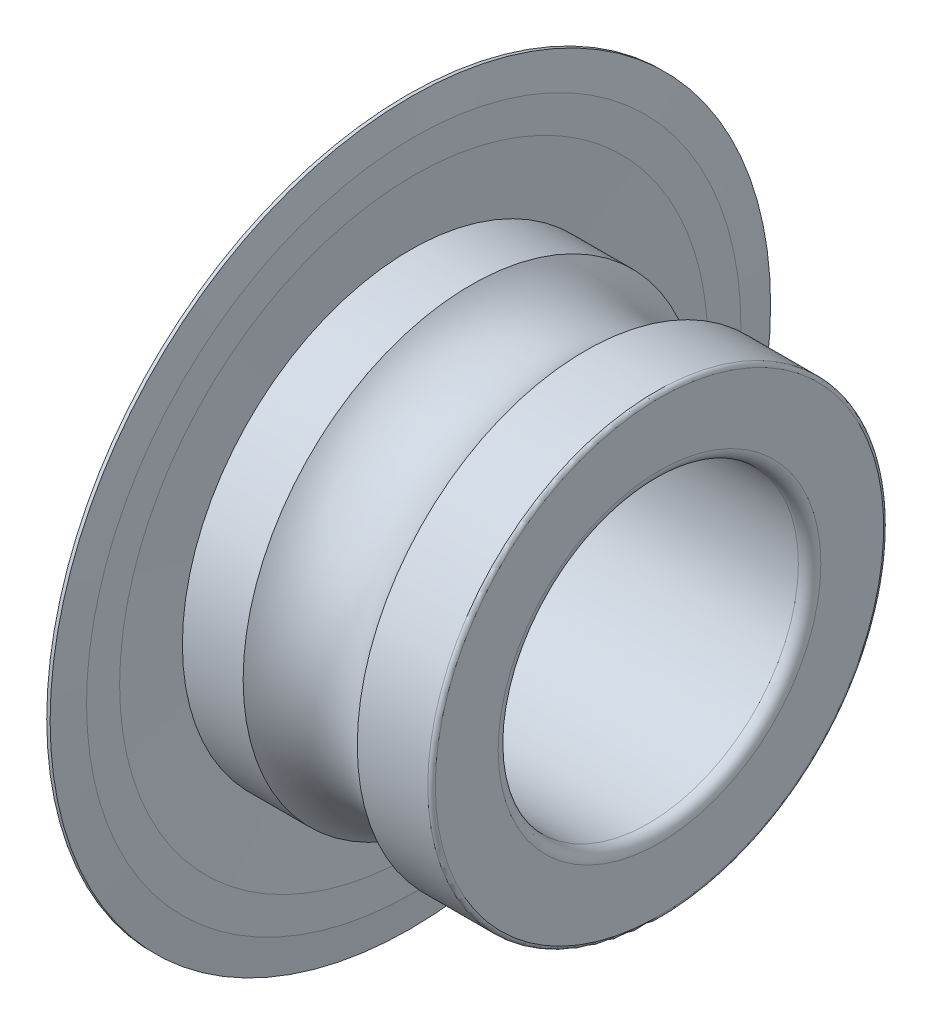
SolidWorks part; units mm, degrees
ref_plane "Front Plane" through (0, 0, 0) normal (0, 0, 1) x (1, 0, 0)
ref_plane "Top Plane" through (0, 0, 0) normal (0, 1, 0) x (1, 0, 0)
ref_plane "Right Plane" through (0, 0, 0) normal (1, 0, 0) x (0, 0, -1)
ref_plane "Plane1"
sketch "Sketch1" plane through (0, 0, 0) normal (0, 0, 1) x (1, 0, 0)
  line L0 (0, 5.975) -> (0, 4.3)
  line L1 (0.3, 4) -> (6.7, 4)
  line L2 (7, 4.3) -> (7, 5.975)
  line L3 (6.9, 6.075) -> (5.0207, 6.075)
  line L4 (1.9793, 6.075) -> (0.1, 6.075)
  line L5 (50, 0) -> (-50, 0) construction
  arc A0 (0, 4.3) -> (0.3, 4) centre (0.3, 4.3) ccw
  arc A1 (6.7, 4) -> (7, 4.3) centre (6.7, 4.3) ccw
  arc A2 (7, 5.975) -> (6.9, 6.075) centre (6.9, 5.975) ccw
  arc A3 (1.9793, 6.075) -> (5.0207, 6.075) centre (3.5, 7.35) ccw
  arc A4 (0.1, 6.075) -> (0, 5.975) centre (0.1, 5.975) ccw
revolve "Revolução1" add sketch "Sketch1" angle 360 about L5
ref_plane "Plane2"
sketch "Sketch2" plane through (0, 0, 0) normal (0, 0, 1) x (1, 0, 0)
  line L0 (0.27, 9.6) -> (0.315, 8.7188)
  line L1 (0.315, 8.7188) -> (0.27, 7.8375)
  line L2 (0.27, 7.8375) -> (0.27, 6.075)
  line L3 (0.27, 6.075) -> (0.36, 6.075)
  line L4 (0.36, 6.075) -> (0.45, 7.8375)
  line L5 (0.45, 7.8375) -> (0.45, 8.7188)
  line L6 (0.45, 8.7188) -> (0.36, 9.6)
  line L7 (0.36, 9.6) -> (0.27, 9.6)
  line L8 (50, 0) -> (-50, 0) construction
revolve "Revolução2" add sketch "Sketch2" angle 360 about L8
